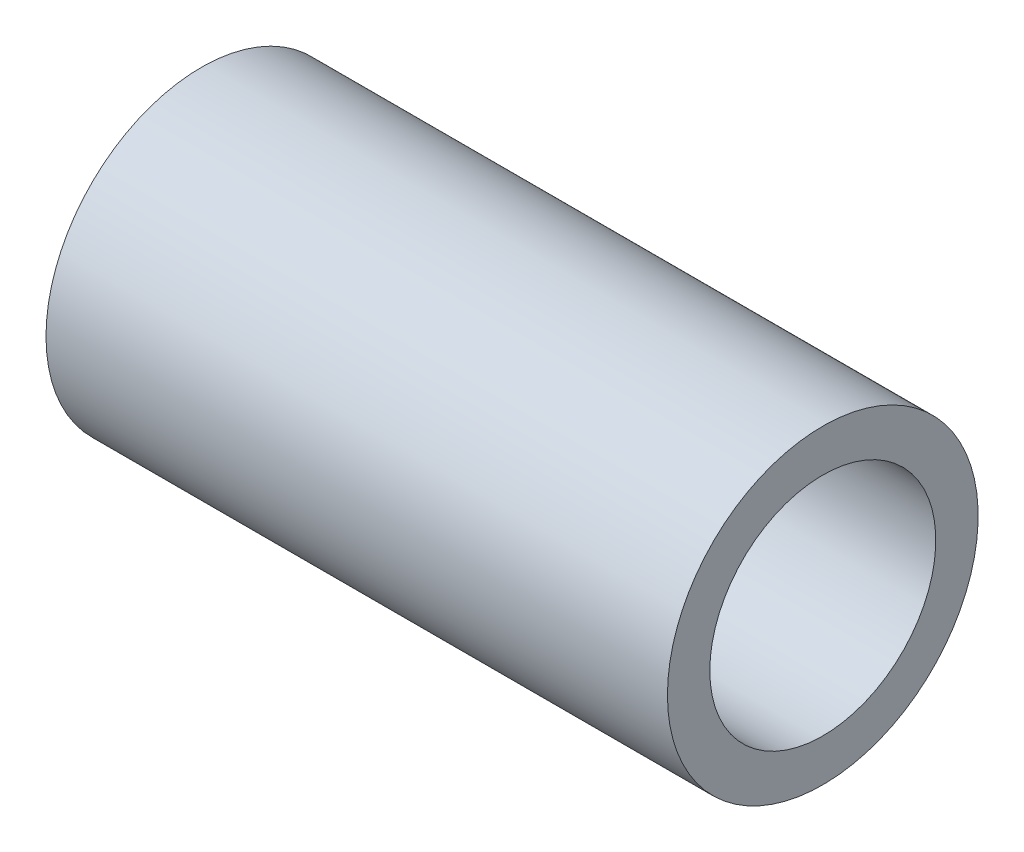
SolidWorks part; units mm, degrees
material "Latão com alto teor de chumbo, UNS C34200"
ref_plane "Plano frontal" through (0, 0, 0) normal (0, 0, 1) x (1, 0, 0)
ref_plane "Plano superior" through (0, 0, 0) normal (0, 1, 0) x (1, 0, 0)
ref_plane "Plano direito" through (0, 0, 0) normal (1, 0, 0) x (0, 0, -1)
sketch "Esboço1" plane through (0, 0, 0) normal (0, 0, 1) x (1, 0, 0)
  line L0 (0, 0) -> (22, 0) construction
  line L2 (0, 4) -> (22, 4)
  line L3 (0, 4) -> (0, 5.5)
  line L4 (0, 5.5) -> (22, 5.5)
  line L5 (22, 4) -> (22, 5.5)
  dimension "D1" = 22
  dimension "D2" = 4
  dimension "D3" = 5.5
revolve "Revolução1" add sketch "Esboço1" angle 360 about L0
